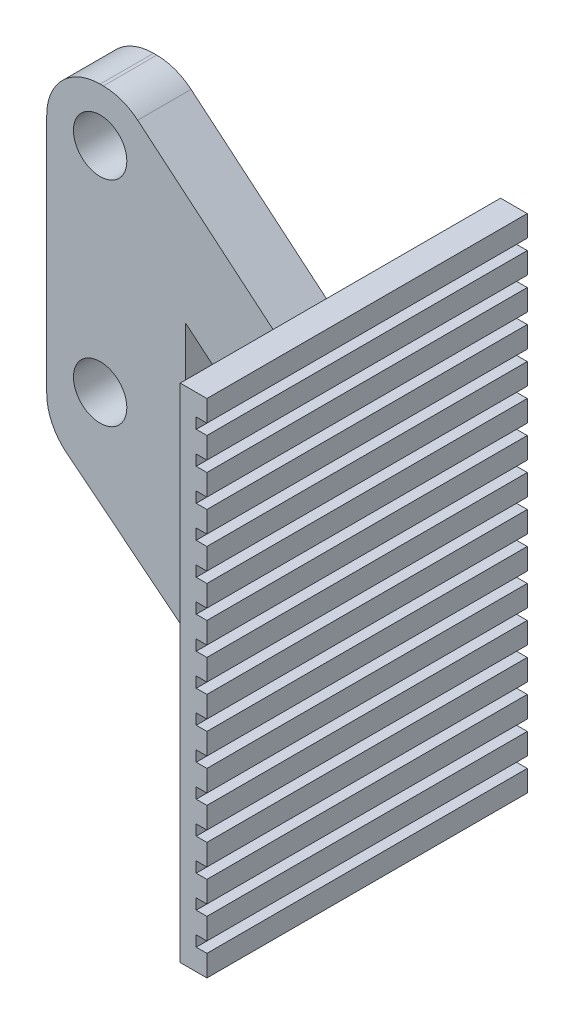
SolidWorks part; units mm, degrees
ref_plane "Front Plane" through (0, 0, 0) normal (0, 0, 1) x (1, 0, 0)
ref_plane "Top Plane" through (0, 0, 0) normal (0, 1, 0) x (1, 0, 0)
ref_plane "Right Plane" through (0, 0, 0) normal (1, 0, 0) x (0, 0, -1)
sketch "Sketch2" plane through (0, 0, 0) normal (0, 0, 1) x (1, 0, 0)
  line L1 (-5, -15) -> (5, -15)
  line L2 (-5, -15) -> (-5, 15)
  line L3 (-5, 15) -> (5, 15)
  line L4 (5, -15) -> (5, 15)
  line L5 (-5, -15) -> (5, 15) construction
  line L6 (-5, 15) -> (5, -15) construction
  circle A0 centre (0, 10) radius 2.5
  circle A1 centre (0, -10) radius 2.5
  point P0 (0, 0)
  dimension "D3" = 5
  dimension "D4" = 5
  dimension "D5" = 10
  dimension "D6" = 10
  dimension "D1" = 30
  dimension "D2" = 10
extrude "Boss-Extrude1" add sketch "Sketch2" along normal blind 5
sketch "Sketch3" plane through (5, 0, 0) normal (1, 0, 0) x (0, 0, -1)
  line L0 (-5, 15) -> (-15.0114, 15) construction
  line L1 (0, -15) -> (12.7295, -15) construction
  line L2 (0, -15) -> (0, 15) construction
  line L3 (-17.5, 15) -> (12.5, 15)
  line L4 (-17.5, 15) -> (-17.5, -15)
  line L5 (-17.5, -15) -> (12.5, -15)
  line L6 (12.5, 15) -> (12.5, -15)
  dimension "D1" = 30
  dimension "D2" = 12.5
extrude "Boss-Extrude2" add sketch "Sketch3" along normal blind 2
sketch "Sketch4" plane through (0, -15, 0) normal (0, -1, 0) x (1, 0, 0)
  line L1 (7, 17.5) -> (5, 17.5)
  line L2 (7, 17.5) -> (7, -12.5)
  line L3 (7, -12.5) -> (5, -12.5)
  line L4 (5, 17.5) -> (5, -12.5)
extrude "Boss-Extrude3" add sketch "Sketch4" along normal blind 20
sketch "Sketch5" plane through (7, 0, 0) normal (1, 0, 0) x (0, 0, -1)
  line L4 (-17.5, 15) -> (-17.5, -35)
  line L5 (-17.5, -35) -> (12.5, -35)
  line L6 (12.5, -35) -> (12.5, 15)
  line L7 (12.5, 15) -> (-17.5, 15)
  line L8 (-17.5, 15) -> (-17.5, -35)
  line L9 (-17.5, -35) -> (12.5, -35)
  line L10 (12.5, -35) -> (12.5, 15)
  line L11 (12.5, 15) -> (-17.5, 15)
  dimension "D1" = 0
extrude "Boss-Extrude4" add sketch "Sketch5" along normal blind 18.5
sketch "Sketch6" plane through (5, 0, 0) normal (-1, 0, 0) x (0, 0, 1)
  line L8 (-12.5, 15) -> (-12.5, -35)
  line L9 (-12.5, -35) -> (17.5, -35)
  line L10 (17.5, -35) -> (17.5, 15)
  line L11 (17.5, 15) -> (5, 15)
  line L12 (5, 15) -> (5, -15)
  line L13 (5, -15) -> (0, -15)
  line L14 (0, -15) -> (0, 15)
  line L15 (0, 15) -> (-12.5, 15)
  line L16 (-12.5, 15) -> (-12.5, -35)
  line L17 (-12.5, -35) -> (17.5, -35)
  line L18 (17.5, -35) -> (17.5, 15)
  line L19 (17.5, 15) -> (5, 15)
  line L20 (5, 15) -> (5, -15)
  line L21 (5, -15) -> (0, -15)
  line L22 (0, -15) -> (0, 15)
  line L23 (0, 15) -> (-12.5, 15)
  dimension "D1" = 0
extrude "Cut-Extrude1" cut sketch "Sketch6" against normal blind 15
sketch "Sketch7" plane through (0, 0, 0) normal (0, 0, 1) x (1, 0, 0)
  line L0 (-5, -15) -> (20, -35)
  line L1 (20, -35) -> (20, -15)
  line L2 (20, -15) -> (-5, -15)
extrude "Boss-Extrude5" add sketch "Sketch7" along normal up to surface (5 mm away) up to face at (7.5, 0, 5)
sketch "Sketch9" plane through (25.5, 0, 0) normal (1, 0, 0) x (0, 0, -1)
  line L4 (12.5, 15) -> (-17.5, 15)
  line L5 (-17.5, 15) -> (-17.5, -35)
  line L6 (-17.5, -35) -> (12.5, -35)
  line L7 (12.5, -35) -> (12.5, 15)
  line L8 (12.5, 15) -> (-17.5, 15)
  line L9 (-17.5, 15) -> (-17.5, -35)
  line L10 (-17.5, -35) -> (12.5, -35)
  line L11 (12.5, -35) -> (12.5, 15)
  dimension "D1" = 0
extrude "Cut-Extrude2" cut sketch "Sketch9" against normal blind 3
sketch "Sketch12" plane through (0, 0, 5) normal (0, 0, 1) x (1, 0, 0)
  line L0 (2.1237, 15) -> (20, 0)
  line L1 (20, 15) -> (-5, 15) construction
  line L2 (20, 15) -> (20, -35) construction
  line L3 (2.1237, 15) -> (20, 15)
  line L4 (20, 15) -> (20, 0)
  dimension "D1" = 50
extrude "Cut-Extrude3" cut sketch "Sketch12" against normal blind 10
fillet "Fillet1" radius 5 3 edges at (2.1237, 15, 2.5) (-5, 15, 2.5) (-5, -15, 2.5)
sketch "Sketch13" plane through (0, 15, 0) normal (0, 1, 0) x (1, 0, 0)
  line L4 (20, 12.5) -> (20, -17.5)
  line L5 (20, -17.5) -> (22.5, -17.5)
  line L6 (22.5, -17.5) -> (22.5, 12.5)
  line L7 (22.5, 12.5) -> (20, 12.5)
  line L8 (20, 12.5) -> (20, -17.5)
  line L9 (20, -17.5) -> (22.5, -17.5)
  line L10 (22.5, -17.5) -> (22.5, 12.5)
  line L11 (22.5, 12.5) -> (20, 12.5)
  dimension "D1" = 0
extrude "Cut-Extrude4" cut sketch "Sketch13" against normal blind 8
sketch "Sketch14" plane through (0, -35, 0) normal (0, -1, 0) x (1, 0, 0)
  line L6 (22.5, -12.5) -> (22.5, 17.5)
  line L7 (22.5, 17.5) -> (20, 17.5)
  line L8 (20, 17.5) -> (20, 5)
  line L9 (20, 5) -> (20, 0)
  line L10 (20, 0) -> (20, -12.5)
  line L11 (20, -12.5) -> (22.5, -12.5)
  line L12 (22.5, -12.5) -> (22.5, 17.5)
  line L13 (22.5, 17.5) -> (20, 17.5)
  line L14 (20, 17.5) -> (20, 5)
  line L15 (20, 5) -> (20, 0)
  line L16 (20, 0) -> (20, -12.5)
  line L17 (20, -12.5) -> (22.5, -12.5)
  dimension "D1" = 0
extrude "Boss-Extrude9" add sketch "Sketch14" along normal blind 5
sketch "Sketch15" plane through (22.5, 0, 0) normal (1, 0, 0) x (0, 0, -1)
  line L0 (-17.5, 7) -> (-17.5, -40) construction
  line L1 (-17.5, 5) -> (12.5, 5)
  line L2 (-17.5, 5) -> (-17.5, 4)
  line L3 (-17.5, 4) -> (12.5, 4)
  line L4 (12.5, 5) -> (12.5, 4)
  line L5 (12.5, -40) -> (12.5, 7) construction
  line L6 (-17.5, 7) -> (12.5, 7) construction
  line L7 (-17.5, 2) -> (-17.5, 1)
  line L8 (-17.5, 2) -> (12.5, 2)
  line L9 (12.5, 2) -> (12.5, 1)
  line L10 (-17.5, 1) -> (12.5, 1)
  line L11 (-17.5, -1) -> (-17.5, -2)
  line L12 (-17.5, -1) -> (12.5, -1)
  line L13 (12.5, -1) -> (12.5, -2)
  line L14 (-17.5, -2) -> (12.5, -2)
  line L15 (-17.5, -4) -> (-17.5, -5)
  line L16 (-17.5, -4) -> (12.5, -4)
  line L17 (12.5, -4) -> (12.5, -5)
  line L18 (-17.5, -5) -> (12.5, -5)
  line L19 (-17.5, -7) -> (-17.5, -8)
  line L20 (-17.5, -7) -> (12.5, -7)
  line L21 (12.5, -7) -> (12.5, -8)
  line L22 (-17.5, -8) -> (12.5, -8)
  line L23 (-17.5, -10) -> (-17.5, -11)
  line L24 (-17.5, -10) -> (12.5, -10)
  line L25 (12.5, -10) -> (12.5, -11)
  line L26 (-17.5, -11) -> (12.5, -11)
  line L27 (-17.5, -13) -> (-17.5, -14)
  line L28 (-17.5, -13) -> (12.5, -13)
  line L29 (12.5, -13) -> (12.5, -14)
  line L30 (-17.5, -14) -> (12.5, -14)
  line L31 (-17.5, -16) -> (-17.5, -17)
  line L32 (-17.5, -16) -> (12.5, -16)
  line L33 (12.5, -16) -> (12.5, -17)
  line L34 (-17.5, -17) -> (12.5, -17)
  line L35 (-17.5, -19) -> (-17.5, -20)
  line L36 (-17.5, -19) -> (12.5, -19)
  line L37 (12.5, -19) -> (12.5, -20)
  line L38 (-17.5, -20) -> (12.5, -20)
  line L39 (-17.5, -22) -> (-17.5, -23)
  line L40 (-17.5, -22) -> (12.5, -22)
  line L41 (12.5, -22) -> (12.5, -23)
  line L42 (-17.5, -23) -> (12.5, -23)
  line L43 (-17.5, -25) -> (-17.5, -26)
  line L44 (-17.5, -25) -> (12.5, -25)
  line L45 (12.5, -25) -> (12.5, -26)
  line L46 (-17.5, -26) -> (12.5, -26)
  line L47 (-17.5, -28) -> (-17.5, -29)
  line L48 (-17.5, -28) -> (12.5, -28)
  line L49 (12.5, -28) -> (12.5, -29)
  line L50 (-17.5, -29) -> (12.5, -29)
  line L51 (-17.5, -31) -> (-17.5, -32)
  line L52 (-17.5, -31) -> (12.5, -31)
  line L53 (12.5, -31) -> (12.5, -32)
  line L54 (-17.5, -32) -> (12.5, -32)
  line L55 (-17.5, -34) -> (-17.5, -35)
  line L56 (-17.5, -34) -> (12.5, -34)
  line L57 (12.5, -34) -> (12.5, -35)
  line L58 (-17.5, -35) -> (12.5, -35)
  line L59 (-17.5, -37) -> (-17.5, -38)
  line L60 (-17.5, -37) -> (12.5, -37)
  line L61 (12.5, -37) -> (12.5, -38)
  line L62 (-17.5, -38) -> (12.5, -38)
  dimension "D1" = 1
  dimension "D2" = 2
  dimension "D3" = 15
extrude "Cut-Extrude5" cut sketch "Sketch15" against normal blind 1
sketch "Sketch17" plane through (0, 0, 5) normal (0, 0, 1) x (1, 0, 0)
  line L1 (20, 7) -> (20, 0)
  line L6 (16, -21.555) -> (16, -7.0869)
  line L7 (16, -7.0869) -> (8, -0.3741)
  line L8 (8, -0.3741) -> (8, -15.155)
  line L9 (8, -15.155) -> (16, -21.555)
  line L10 (20, -35) -> (-3.1235, -16.5012) construction
  line L11 (3.5178, 13.8302) -> (20, 0) construction
  line L12 (20, -40) -> (20, 7) construction
  dimension "D1" = 8
  dimension "D2" = 8
  dimension "D3" = 4
  dimension "D4" = 8
extrude "Cut-Extrude6" cut sketch "Sketch17" against normal through all contours L8 L9 L6 L7
